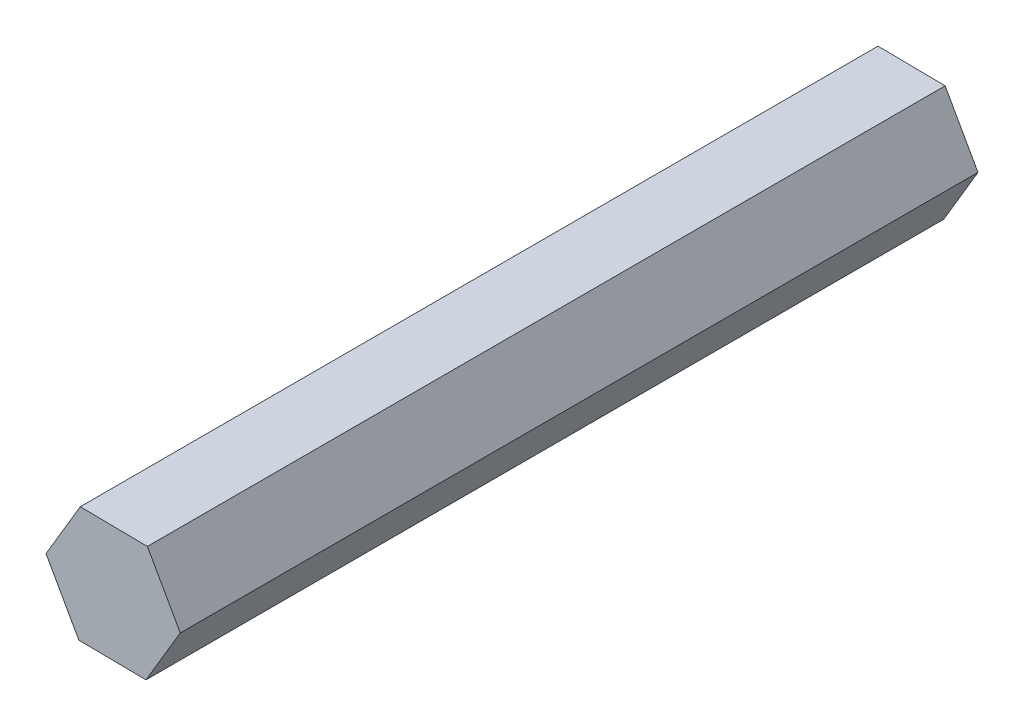
SolidWorks part; units mm, degrees
ref_plane "Front Plane" through (0, 0, 0) normal (0, 0, 1) x (1, 0, 0)
ref_plane "Top Plane" through (0, 0, 0) normal (0, 1, 0) x (1, 0, 0)
ref_plane "Right Plane" through (0, 0, 0) normal (1, 0, 0) x (0, 0, -1)
sketch "Sketch1" plane through (0, 0, 0) normal (0, 0, 1) x (1, 0, 0)
  line L1 (2.8069, 4.729) -> (-2.692, 4.7953)
  line L2 (-2.692, 4.7953) -> (-5.4989, 0.0663)
  line L3 (-5.4989, 0.0663) -> (-2.8069, -4.729)
  line L4 (-2.8069, -4.729) -> (2.692, -4.7953)
  line L5 (2.692, -4.7953) -> (5.4989, -0.0663)
  line L6 (5.4989, -0.0663) -> (2.8069, 4.729)
  circle A0 centre (0, 0) radius 4.7625 construction
  dimension "D1" = 9.525
extrude "Boss-Extrude1" add sketch "Sketch1" along normal blind 65.3542
